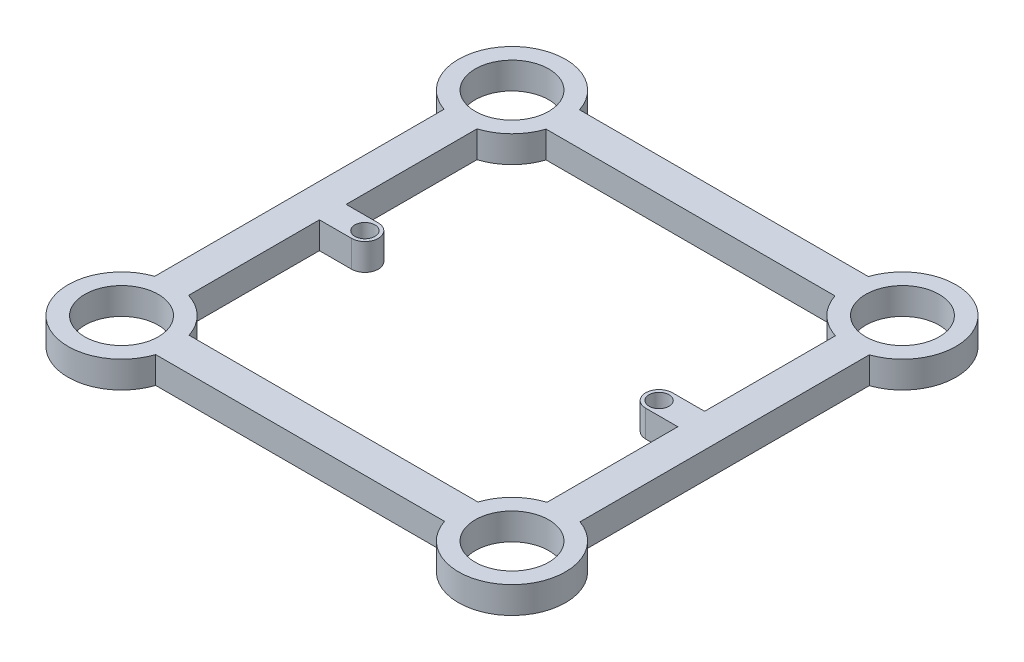
SolidWorks part; units mm, degrees
ref_plane "Front Plane" through (0, 0, 0) normal (0, 0, 1) x (1, 0, 0)
ref_plane "Top Plane" through (0, 0, 0) normal (0, 1, 0) x (1, 0, 0)
ref_plane "Right Plane" through (0, 0, 0) normal (1, 0, 0) x (0, 0, -1)
sketch "Sketch1" plane through (0, 0, 0) normal (0, 1, 0) x (1, 0, 0)
  line L0 (-12.6997, 0) -> (-14.9222, 0) construction
  line L1 (-20.1953, 13.7385) -> (-20.1953, -13.7385)
  line L2 (-17.0203, 13.6953) -> (-17.0203, 1.27)
  line L3 (17.0203, 13.6953) -> (17.0203, 1.27)
  line L4 (20.1953, 13.7385) -> (20.1953, -13.7385)
  line L5 (0, 0) -> (18.542, 18.542) construction
  line L6 (-18.542, 18.542) -> (0, 0) construction
  line L7 (-13.7164, 20.1295) -> (13.7164, 20.1295)
  line L8 (-13.7164, 16.9545) -> (13.7164, 16.9545)
  line L9 (-18.542, -18.542) -> (0, 0) construction
  line L10 (0, 0) -> (18.542, -18.542) construction
  line L11 (13.9697, -1.27) -> (17.0203, -1.27)
  line L12 (-13.9697, 1.27) -> (-17.0203, 1.27)
  line L13 (-13.9697, -1.27) -> (-17.0203, -1.27)
  line L14 (13.9697, 1.27) -> (17.0203, 1.27)
  line L15 (-13.7164, -16.9545) -> (13.7164, -16.9545)
  line L16 (-13.7164, -20.1295) -> (13.7164, -20.1295)
  line L18 (17.0203, -13.6953) -> (17.0203, -1.27)
  line L19 (-17.0203, -13.6953) -> (-17.0203, -1.27)
  arc A0 (-17.0203, 13.6953) -> (-13.7164, 16.9545) centre (-18.542, 18.542) ccw
  arc A1 (20.1953, 13.7385) -> (13.7164, 20.1295) centre (18.542, 18.542) ccw
  circle A2 centre (18.542, -18.542) radius 3.4925
  circle A3 centre (-18.542, -18.542) radius 3.4925
  arc A4 (-13.7164, 20.1295) -> (-20.1953, 13.7385) centre (-18.542, 18.542) ccw
  arc A5 (13.7164, 16.9545) -> (17.0203, 13.6953) centre (18.542, 18.542) ccw
  arc A6 (13.7164, -16.9545) -> (17.0203, -13.6953) centre (18.542, -18.542) cw
  arc A7 (-13.7164, -20.1295) -> (-20.1953, -13.7385) centre (-18.542, -18.542) cw
  circle A8 centre (-18.542, 18.542) radius 3.4925
  circle A9 centre (18.542, 18.542) radius 3.4925
  arc A10 (20.1953, -13.7385) -> (13.7164, -20.1295) centre (18.542, -18.542) cw
  arc A11 (-17.0203, -13.6953) -> (-13.7164, -16.9545) centre (-18.542, -18.542) cw
  arc A12 (-13.9697, -1.27) -> (-13.9697, 1.27) centre (-13.9697, 0) ccw
  arc A13 (13.9697, 1.27) -> (13.9697, -1.27) centre (13.9697, 0) ccw
  circle A14 centre (-13.9697, 0) radius 0.9525
  circle A15 centre (13.9697, 0) radius 0.9525
  point P0 (0, 0)
  dimension "D1" = 6.985
  dimension "D3" = 10.16
  dimension "D11" = 1.905
  dimension "D2" = 3.0506
  dimension "D4" = 3.175
  dimension "D7" = 3.175
extrude "Boss-Extrude1" add sketch "Sketch1" along normal blind 2.54
